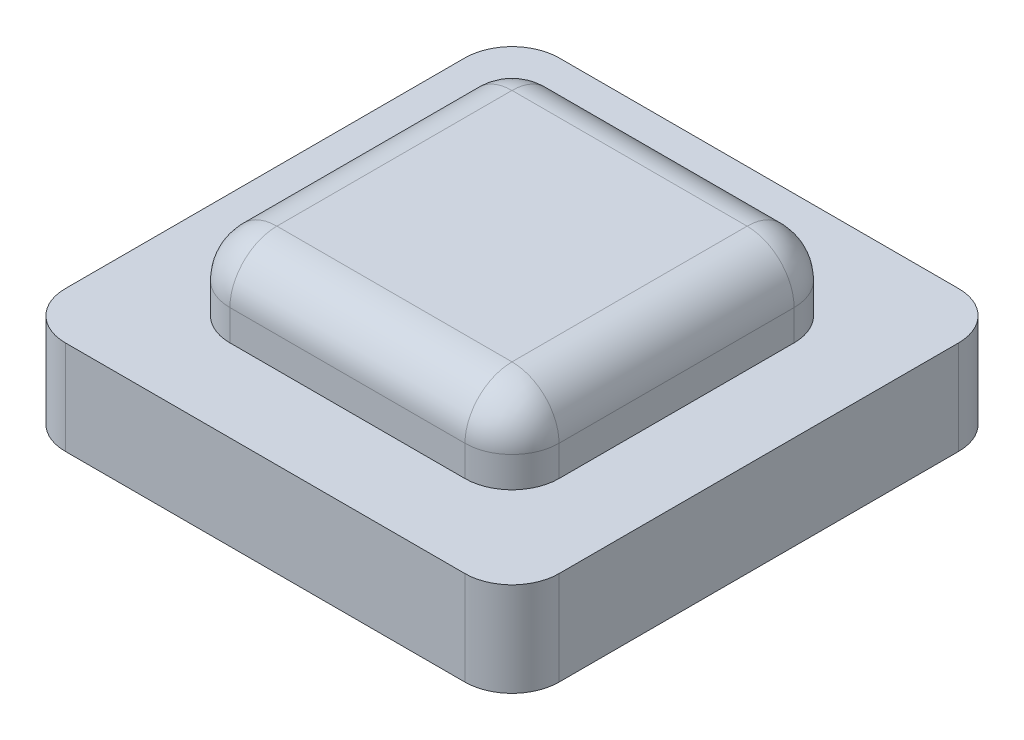
SolidWorks part; units mm, degrees
material "6063-T6"
ref_plane "Front Plane" through (0, 0, 0) normal (0, 0, 1) x (1, 0, 0)
ref_plane "Top Plane" through (0, 0, 0) normal (0, 1, 0) x (1, 0, 0)
ref_plane "Right Plane" through (0, 0, 0) normal (1, 0, 0) x (0, 0, -1)
sketch "Sketch1" plane through (0, 0, 0) normal (0, 1, 0) x (1, 0, 0)
  line L1 (-10.5, 10.5) -> (10.5, 10.5)
  line L2 (-10.5, 10.5) -> (-10.5, -10.5)
  line L3 (-10.5, -10.5) -> (10.5, -10.5)
  line L4 (10.5, 10.5) -> (10.5, -10.5)
  line L5 (-10.5, 10.5) -> (10.5, -10.5) construction
  line L6 (-10.5, -10.5) -> (10.5, 10.5) construction
  point P0 (0, 0)
  dimension "D1" = 21
extrude "Boss-Extrude1" add sketch "Sketch1" along normal blind 4
sketch "Sketch2" plane through (0, 0, 0) normal (0, -1, 0) x (1, 0, 0)
  line L1 (-4.75, 4.75) -> (4.75, 4.75)
  line L2 (-4.75, 4.75) -> (-4.75, -4.75)
  line L3 (-4.75, -4.75) -> (4.75, -4.75)
  line L4 (4.75, 4.75) -> (4.75, -4.75)
  line L5 (-4.75, 4.75) -> (4.75, -4.75) construction
  line L6 (-4.75, -4.75) -> (4.75, 4.75) construction
  point P0 (0, 0)
  dimension "D1" = 9.5
extrude "Boss-Extrude2" add sketch "Sketch2" along normal blind 3.7
sketch "Sketch3" plane through (0, 4, 0) normal (0, 1, 0) x (1, 0, 0)
  line L1 (-7, 7) -> (7, 7)
  line L2 (-7, 7) -> (-7, -7)
  line L3 (-7, -7) -> (7, -7)
  line L4 (7, 7) -> (7, -7)
  line L5 (-7, 7) -> (7, -7) construction
  line L6 (-7, -7) -> (7, 7) construction
  point P0 (0, 0)
  dimension "D1" = 14
extrude "Boss-Extrude3" add sketch "Sketch3" along normal blind 3.3
fillet "Fillet1" radius 2 4 edges at (-10.5, 2, -10.5) (10.5, 2, -10.5) (10.5, 2, 10.5) (-10.5, 2, 10.5)
fillet "Fillet2" radius 2 8 edges at (0, 7.3, 7) (7, 7.3, 0) (0, 7.3, -7) (-7, 7.3, 0) (-7, 5.65, 7) (-7, 5.65, -7) (7, 5.65, -7) (7, 5.65, 7)
fillet "Fillet3" radius 2 8 edges at (-4.75, -1.85, -4.75) (-4.75, -1.85, 4.75) (4.75, -1.85, 4.75) (4.75, -1.85, -4.75) (0, -3.7, -4.75) (-4.75, -3.7, 0) (0, -3.7, 4.75) (4.75, -3.7, 0)
equation "\"chip_size\"= 10mm"
equation "\"hold_edge\"= 1mm"
equation "\"holder_size\"= 32.2mm"
equation "\"M2P5\"= 2.5"
equation "\"height_SMA\"= 6.5"
equation "\"tube_SMA\"= 4mm"
equation "\"separation_SMA\"= 11"
equation "\"cavity_size\"=21"
equation "\"PCB_thickness\"= 0.51"
equation "\"PCB_Cu_thickness\"= 0.035"
equation "\"fillet_out\"= 3mm"
equation "\"fillet_cavity_top\"= 2"
equation "\"fillet_chip_sink\"= 0.4"
equation "\"fillet_cavity_bottom\"= 1"
equation "\"w_1\"= 1"
equation "\"s_1\"= 0.64"
equation "\"w_2\"= 0.6"
equation "\"s_2\"= 0.11"
equation "\"d_via\"= 0.25"
equation "\"D1@Sketch1\"=\"cavity_size\""
equation "\"D1@Sketch2\"=\"chip_size\"-0.5"
